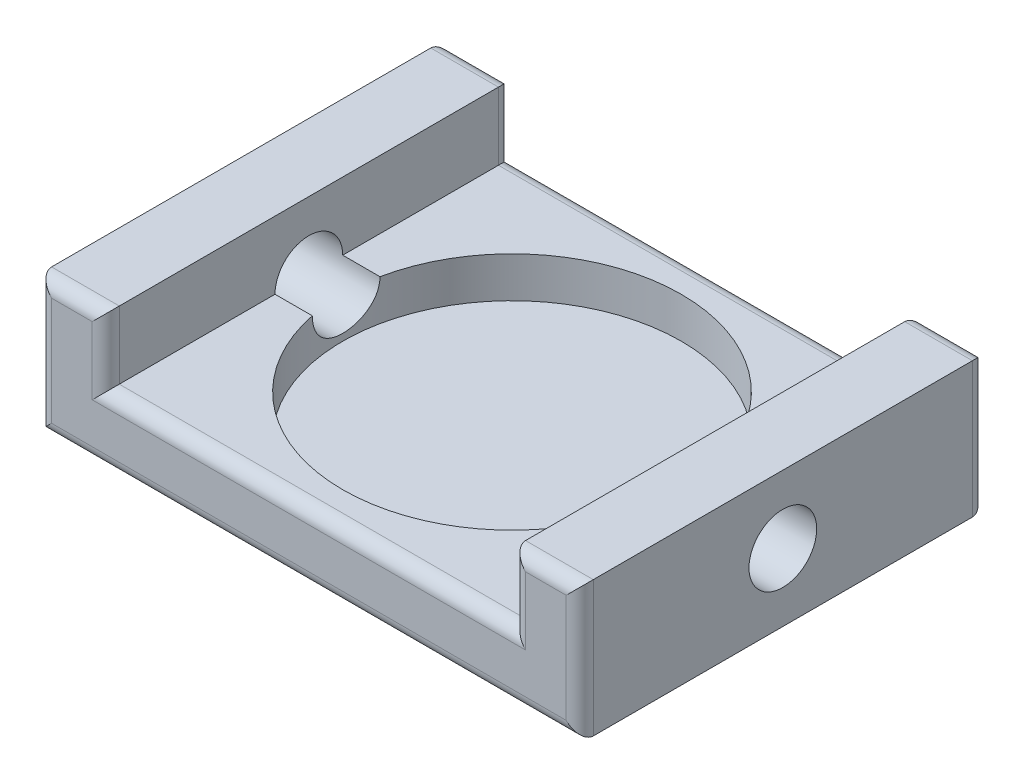
SolidWorks part; units mm, degrees
ref_plane "前视基准面" through (0, 0, 0) normal (0, 0, 1) x (1, 0, 0)
ref_plane "上视基准面" through (0, 0, 0) normal (0, 1, 0) x (1, 0, 0)
ref_plane "右视基准面" through (0, 0, 0) normal (1, 0, 0) x (0, 0, -1)
sketch "草图1" plane through (0, 0, 0) normal (0, 1, 0) x (1, 0, 0)
  line L0 (0, 0) -> (40, 0)
  line L1 (40, 0) -> (40, 30)
  line L2 (40, 30) -> (0, 30)
  line L3 (0, 30) -> (0, 0)
extrude "凸台-拉伸1" add sketch "草图1" along normal blind 10
sketch "草图3" plane through (0, 0, 0) normal (-1, 0, 0) x (0, 0, 1)
  line L0 (-15, 10) -> (-15, 5)
  line L1 (-30, 10) -> (0, 10) construction
  circle A0 centre (-15, 5) radius 2.5
extrude "切除-拉伸1" cut sketch "草图3" against normal through all
sketch "草图4" plane through (0, 10, 0) normal (0, 1, 0) x (1, 0, 0)
  line L0 (20, 30) -> (5, 30)
  line L1 (40, 30) -> (0, 30) construction
  line L2 (5, 30) -> (5, 0)
  line L3 (0, 0) -> (40, 0) construction
  line L4 (5, 0) -> (35, 0)
  line L5 (35, 0) -> (35, 30)
  line L6 (35, 30) -> (20, 30)
extrude "切除-拉伸2" cut sketch "草图4" against normal blind 5
sketch "草图5" plane through (0, 5, 0) normal (0, 1, 0) x (1, 0, 0)
  circle A0 centre (20, 15) radius 12.5
extrude "切除-拉伸3" cut sketch "草图5" against normal blind 3
fillet "圆角1" radius 1 16 edges at (40, 5, 0) (20, 0, 0) (0, 5, 0) (2.5, 10, 0) (5, 7.5, 0) (20, 5, 0) (35, 7.5, 0) (37.5, 10, 0) (5, 7.5, -30) (2.5, 10, -30) (0, 5, -30) (20, 0, -30) (40, 5, -30) (37.5, 10, -30) (35, 7.5, -30) (20, 5, -30)
